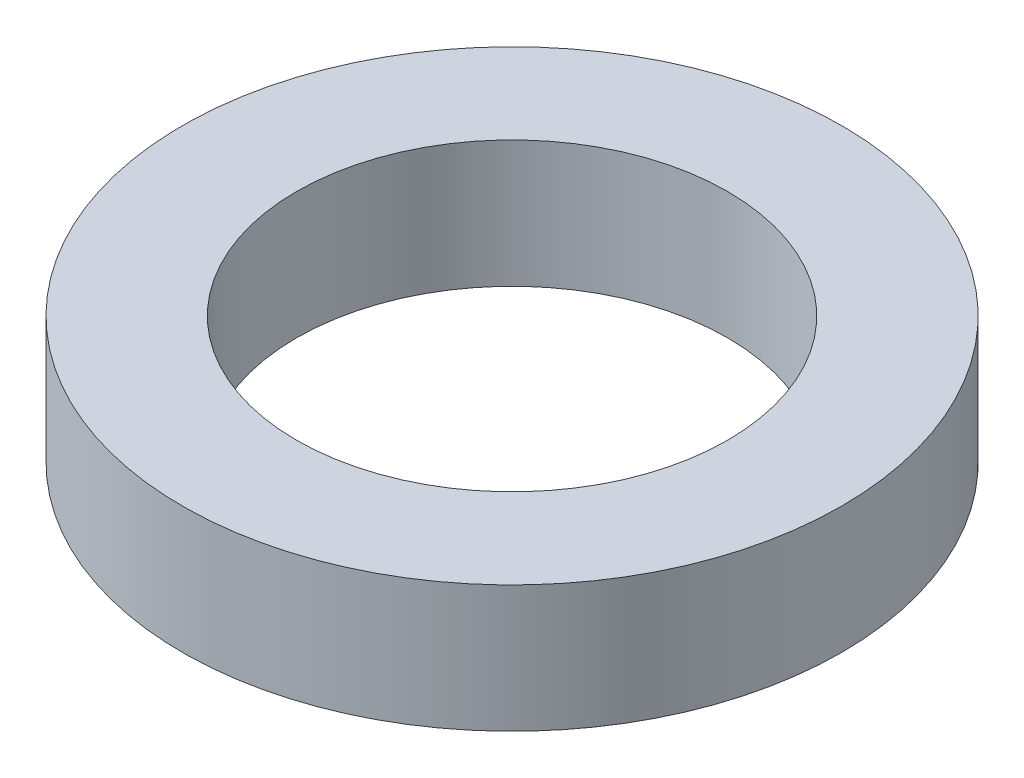
SolidWorks part; units mm, degrees
ref_plane "前视基准面" through (0, 0, 0) normal (0, 0, 1) x (1, 0, 0)
ref_plane "上视基准面" through (0, 0, 0) normal (0, 1, 0) x (1, 0, 0)
ref_plane "右视基准面" through (0, 0, 0) normal (1, 0, 0) x (0, 0, -1)
other "Configuration Table"
sketch "草图1" plane through (0, 0, 0) normal (0, 1, 0) x (1, 0, 0)
  circle A0 centre (0, 0) radius 8.5
  dimension "D1" = 17
extrude "拉伸-薄壁1" add sketch "草图1" along normal blind 5 thin
